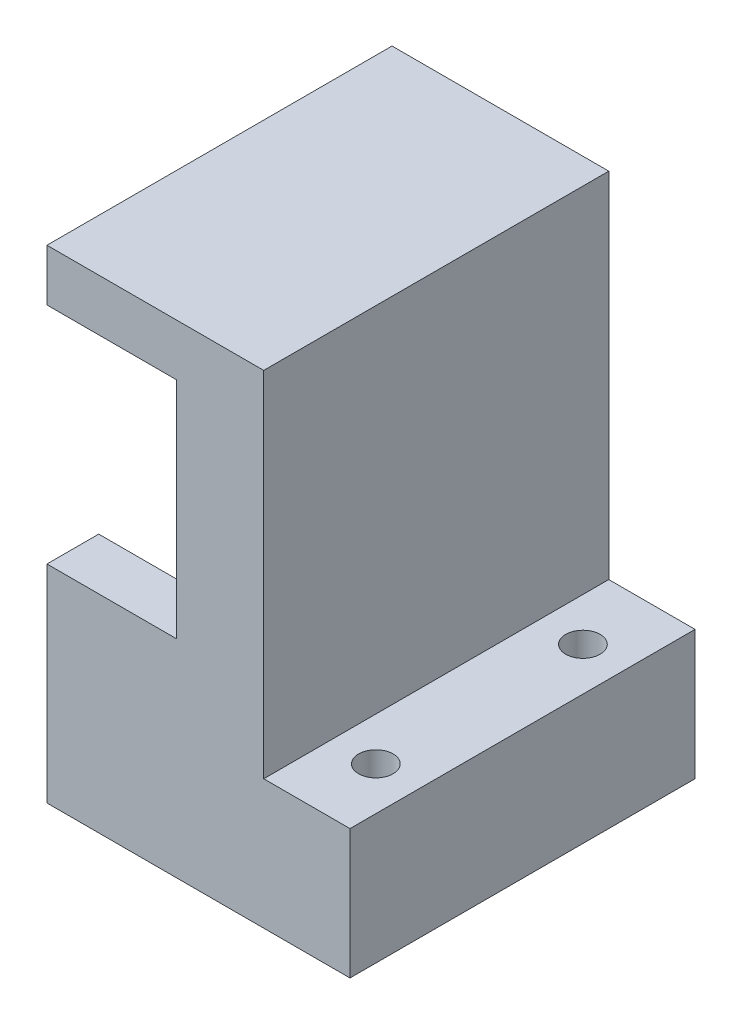
SolidWorks part; units mm, degrees
ref_plane "Plan de face" through (0, 0, 0) normal (0, 0, 1) x (1, 0, 0)
ref_plane "Plan de dessus" through (0, 0, 0) normal (0, 1, 0) x (1, 0, 0)
ref_plane "Plan de droite" through (0, 0, 0) normal (1, 0, 0) x (0, 0, -1)
sketch "Esquisse1" plane through (0, 0, 0) normal (0, 0, 1) x (1, 0, 0)
  line L0 (0, 0) -> (-15, 0)
  line L3 (10.127, 0) -> (10.127, -41)
  line L4 (10.127, -41) -> (20.127, -41)
  line L5 (20.127, -41) -> (20.127, -56)
  line L6 (20.127, -56) -> (-15, -56)
  line L7 (-15, -56) -> (-15, -41)
  line L8 (-15, -41) -> (0, -41)
  line L9 (0, -41) -> (0, -6)
  line L10 (0, -6) -> (-15, -6)
  line L11 (-15, -6) -> (-15, 0)
  line L12 (0, 0) -> (10.127, 0)
  dimension "D3" = 6
  dimension "D4" = 35
  dimension "D5" = 15
  dimension "D6" = 10
  dimension "D7" = 15
  dimension "D8" = 15
extrude "Boss.-Extru.1" add sketch "Esquisse1" along normal blind 40
sketch "Sketch1" plane through (0, -41, 0) normal (0, 1, 0) x (1, 0, 0)
  line L0 (10.127, -40) -> (10.127, 0) construction
  line L1 (10.127, -40) -> (10.127, 0) construction
  line L2 (20.127, 0) -> (10.127, 0) construction
  line L3 (20.127, -40) -> (10.127, -40) construction
  circle A0 centre (15.127, -8) radius 2
  circle A1 centre (15.127, -32) radius 2
  dimension "D1" = 4
  dimension "D2" = 4
  dimension "D3" = 5
  dimension "D4" = 5
  dimension "D5" = 8
  dimension "D6" = 8
extrude "Cut-Extrude1" cut sketch "Sketch1" against normal blind 29
sketch "Sketch2" plane through (0, 0, 40) normal (0, 0, 1) x (1, 0, 0)
  line L0 (0, -6) -> (0, -41) construction
  line L1 (0, -32) -> (-15, -32)
  line L2 (0, -32) -> (0, -41)
  line L3 (0, -41) -> (-15, -41)
  line L4 (-15, -32) -> (-15, -41)
  dimension "D1" = 9
extrude "Boss-Extrude1" add sketch "Sketch2" against normal blind 6
